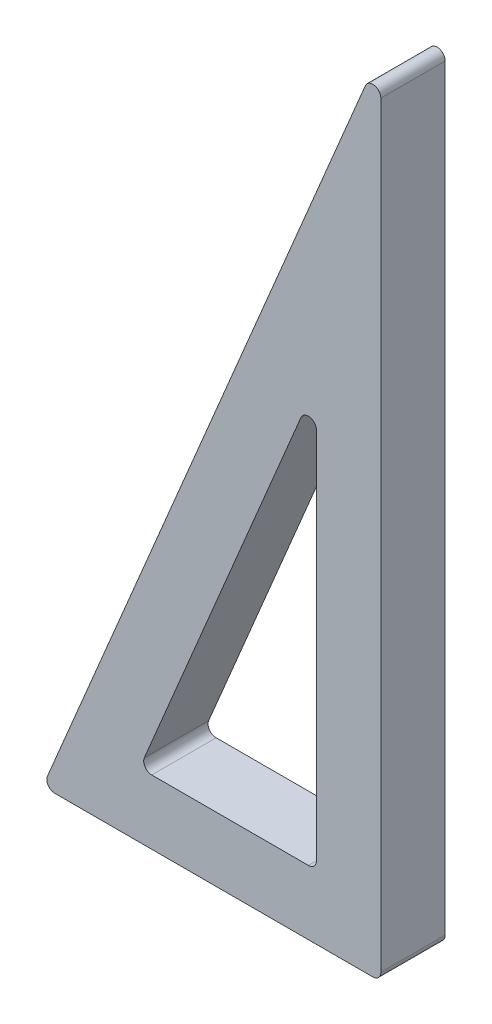
SolidWorks part; units mm, degrees
ref_plane "정면" through (0, 0, 0) normal (0, 0, 1) x (1, 0, 0)
ref_plane "윗면" through (0, 0, 0) normal (0, 1, 0) x (1, 0, 0)
ref_plane "우측면" through (0, 0, 0) normal (1, 0, 0) x (0, 0, -1)
sketch "스케치1" plane through (0, 0, 0) normal (0, 0, 1) x (1, 0, 0)
  line L0 (21, 50) -> (-21, -50)
  line L1 (-21, 50) -> (21, 50)
  line L2 (-21, 50) -> (-21, -50)
  line L3 (-21, -50) -> (21, -50)
  line L4 (21, 50) -> (21, -50)
  line L5 (-21, 50) -> (21, -50) construction
  line L6 (-21, -50) -> (21, 50) construction
  point P0 (0, 0)
  dimension "D1" = 42
  dimension "D2" = 100
extrude "보스-돌출1" add sketch "스케치1" along normal blind 8 contours L4 L0 L3
fillet "필렛1" radius 1 3 edges at (21, -50, 4) (-21, -50, 4) (21, 50, 4)
sketch "스케치2" plane through (0, 0, 8) normal (0, 0, 1) x (1, 0, 0)
  line L0 (-8.963, -42) -> (13, -42)
  line L1 (13, -42) -> (13, 10.293)
  line L2 (13, 10.293) -> (-8.963, -42)
  line L3 (-19.4954, -50) -> (20, -50)
  line L4 (21, -49) -> (21, 45.0366)
  line L5 (19.078, 45.4239) -> (-20.4174, -48.6128)
  line L6 (-19.4954, -50) -> (20, -50)
  line L7 (21, -49) -> (21, 45.0366)
  line L8 (19.078, 45.4239) -> (-20.4174, -48.6128)
  arc A0 (13, -42) -> (13, -42) centre (13, -42) ccw
  arc A1 (13, 10.293) -> (13, 10.293) centre (13, 10.293) ccw
  arc A2 (-8.963, -42) -> (-8.963, -42) centre (-8.963, -42) ccw
  arc A3 (20, -50) -> (21, -49) centre (20, -49) ccw
  arc A4 (21, 45.0366) -> (19.078, 45.4239) centre (20, 45.0366) ccw
  arc A5 (-20.4174, -48.6128) -> (-19.4954, -50) centre (-19.4954, -49) ccw
  arc A6 (20, -50) -> (21, -49) centre (20, -49) ccw
  arc A7 (21, 45.0366) -> (19.078, 45.4239) centre (20, 45.0366) ccw
  arc A8 (-20.4174, -48.6128) -> (-19.4954, -50) centre (-19.4954, -49) ccw
  dimension "D1" = 0
  dimension "D2" = 8
extrude "컷-돌출1" cut sketch "스케치2" against normal blind 36 contours L1 L2 L0
fillet "필렛2" radius 1 3 edges at (13, 10.293, 4) (13, -42, 4) (-8.963, -42, 4)
